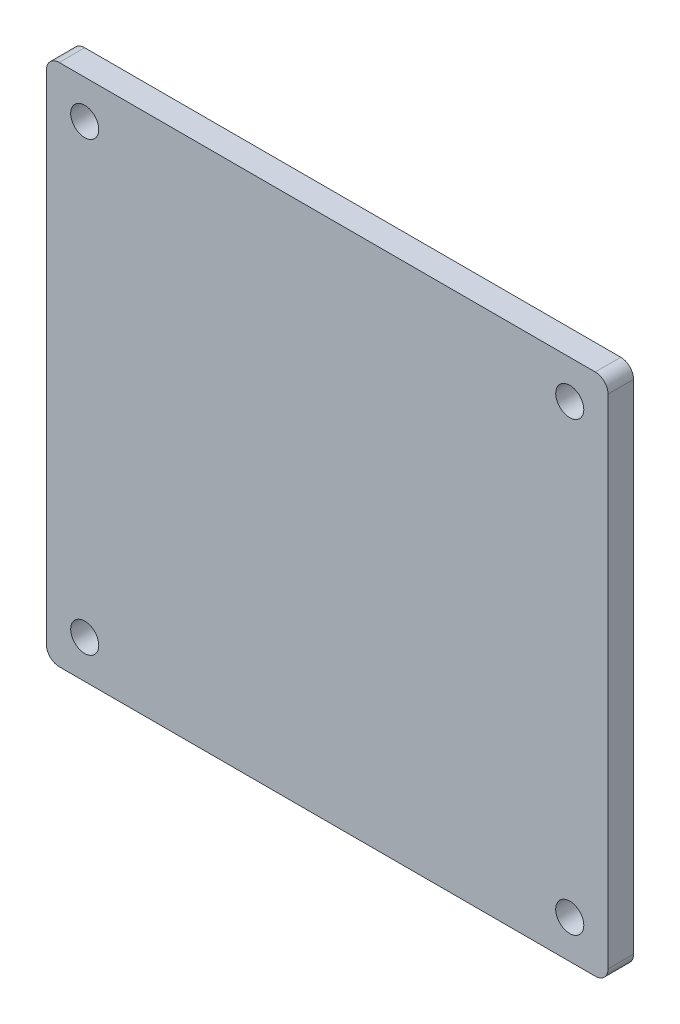
SolidWorks part; units mm, degrees
material "玻璃"
ref_plane "前视基准面" through (0, 0, 0) normal (0, 0, 1) x (1, 0, 0)
ref_plane "上视基准面" through (0, 0, 0) normal (0, 1, 0) x (1, 0, 0)
ref_plane "右视基准面" through (0, 0, 0) normal (1, 0, 0) x (0, 0, -1)
sketch "草图1" plane through (0, 0, 0) normal (0, 0, 1) x (1, 0, 0)
  line L1 (-22, -20.5) -> (22, -20.5)
  line L2 (-22, -20.5) -> (-22, 20.5)
  line L3 (-22, 20.5) -> (22, 20.5)
  line L4 (22, -20.5) -> (22, 20.5)
  line L5 (-22, -20.5) -> (22, 20.5) construction
  line L6 (-22, 20.5) -> (22, -20.5) construction
  point P0 (0, 0)
  dimension "D1" = 44
  dimension "D2" = 41
extrude "凸台-拉伸1" add sketch "草图1" along normal blind 2
sketch "草图2" plane through (0, 0, 2) normal (0, 0, 1) x (1, 0, 0)
  line L2 (-19, -17.5) -> (19, -17.5) construction
  line L3 (-19, -17.5) -> (-19, 17.5) construction
  line L4 (-19, 17.5) -> (19, 17.5) construction
  line L5 (19, -17.5) -> (19, 17.5) construction
  line L6 (-19, -17.5) -> (19, 17.5) construction
  line L7 (-19, 17.5) -> (19, -17.5) construction
  circle A0 centre (19, 17.5) radius 1.1
  circle A1 centre (-19, 17.5) radius 1.1
  circle A2 centre (-19, -17.5) radius 1.1
  circle A3 centre (19, -17.5) radius 1.1
  point P2 (0, 0)
  dimension "D3" = 2.2
  dimension "D1" = 35
  dimension "D2" = 38
extrude "切除-拉伸1" cut sketch "草图2" against normal blind 2
fillet "圆角1" radius 1 4 edges at (22, -20.5, 1) (-22, -20.5, 1) (-22, 20.5, 1) (22, 20.5, 1)
